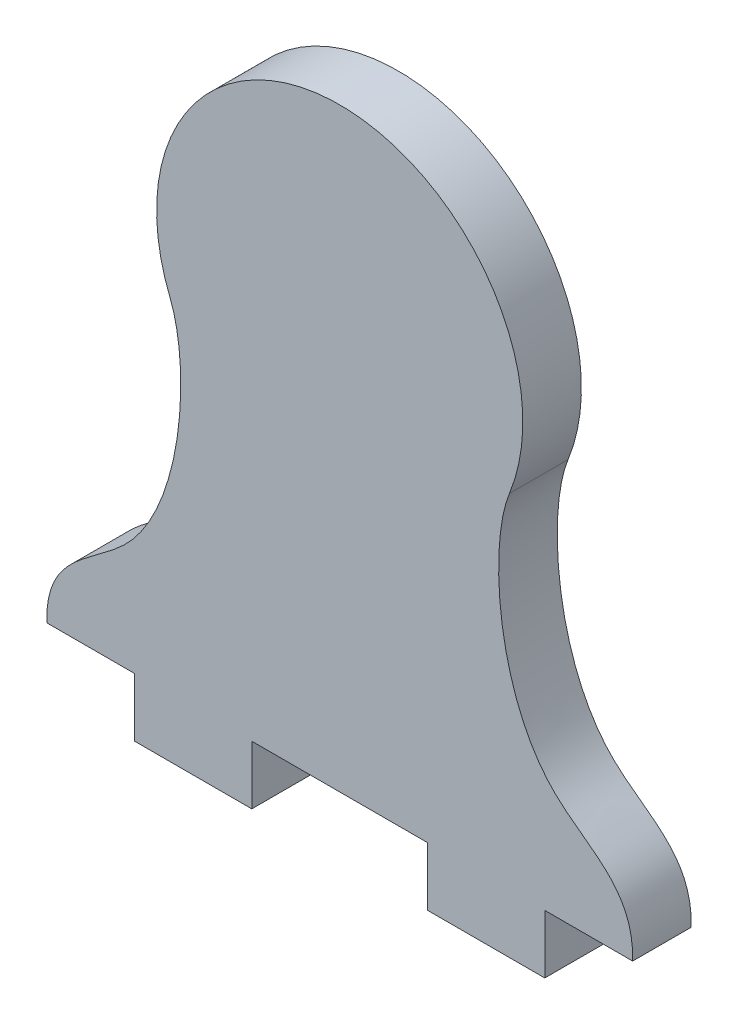
SolidWorks part; units mm, degrees
ref_plane "Front Plane" through (0, 0, 0) normal (0, 0, 1) x (1, 0, 0)
ref_plane "Top Plane" through (0, 0, 0) normal (0, 1, 0) x (1, 0, 0)
ref_plane "Right Plane" through (0, 0, 0) normal (1, 0, 0) x (0, 0, -1)
sketch "Sketch1" plane through (0, 0, 0) normal (0, 0, 1) x (1, 0, 0)
  line L0 (0, 0) -> (0, 43.925) construction
  line L1 (6, 0) -> (-6, 0)
  line L2 (-14, 0) -> (-20, 0)
  line L3 (14, 0) -> (14, -4)
  line L4 (-6, 0) -> (-6, -4)
  line L5 (-6, -4) -> (-14, -4)
  line L6 (-14, 0) -> (-14, -4)
  line L7 (6, -4) -> (14, -4)
  line L8 (6, 0) -> (6, -4)
  line L9 (14, 0) -> (20, 0)
  arc A0 (11.5731, 23.408) -> (-11.5731, 23.408) centre (0, 28.1317) ccw
  spline S0 degree 3 poles (-20, 0) (-20.1199, 4.3145) (-10.8687, 6.6032) (-10.176, 19.9678) (-11.5829, 23.4322) (-11.5878, 23.4442) knots 0 0 0 0 0.217805 0.603788 0.605134 0.605134 0.605134 0.605134
  spline S1 degree 3 poles (20, 0) (20.1199, 4.3145) (10.8687, 6.6032) (10.176, 19.9678) (11.5829, 23.4322) (11.5878, 23.4442) knots 0 0 0 0 0.217805 0.603788 0.605134 0.605134 0.605134 0.605134
  dimension "D2" = 25
  dimension "D1" = 20
  dimension "D3" = 4
  dimension "D4" = 6
  dimension "D5" = 8
extrude "Boss-Extrude1" add sketch "Sketch1" along normal blind 4 contours L1 L0 A0 S0 L2 L6 L5 L4 | L0 L1 L8 L7 L3 L9 S1 A0
